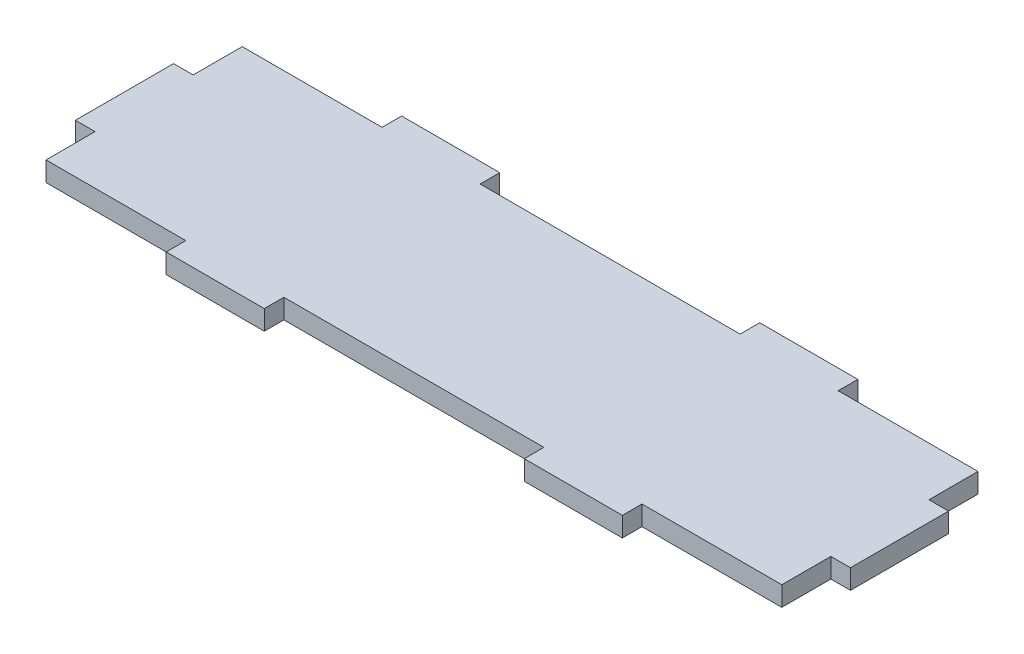
SolidWorks part; units mm, degrees
ref_plane "Alzado" through (0, 0, 0) normal (0, 0, 1) x (1, 0, 0)
ref_plane "Planta" through (0, 0, 0) normal (0, 1, 0) x (1, 0, 0)
ref_plane "Vista lateral" through (0, 0, 0) normal (1, 0, 0) x (0, 0, -1)
sketch "Croquis1" plane through (0, 0, 0) normal (0, 1, 0) x (1, 0, 0)
  line L0 (75, 0) -> (75, 40) construction
  line L1 (0, 0) -> (28.5, 0)
  line L2 (0, 0) -> (0, 10)
  line L3 (0, 40) -> (28.5, 40)
  line L4 (150, 0) -> (150, 10)
  line L6 (28.5, 40) -> (28.5, 44)
  line L7 (28.5, 44) -> (48.5, 44)
  line L8 (48.5, 40) -> (48.5, 44)
  line L10 (28.5, 0) -> (28.5, -4)
  line L11 (28.5, -4) -> (48.5, -4)
  line L12 (48.5, 0) -> (48.5, -4)
  line L13 (0, 10) -> (-4, 10)
  line L15 (0, 30) -> (-4, 30)
  line L16 (-4, 10) -> (-4, 30)
  line L17 (75, 20) -> (0, 20) construction
  line L18 (-4, 20) -> (0, 20) construction
  line L19 (37.5, 20) -> (37.5, 44) construction
  line L20 (37.5, 20) -> (37.5, -4) construction
  line L21 (121.5, 40) -> (121.5, 44)
  line L22 (101.5, 40) -> (101.5, 44)
  line L23 (121.5, 44) -> (101.5, 44)
  line L24 (101.5, 0) -> (101.5, -4)
  line L25 (121.5, -4) -> (101.5, -4)
  line L26 (121.5, 0) -> (121.5, -4)
  line L27 (150, 10) -> (154, 10)
  line L28 (154, 10) -> (154, 30)
  line L29 (150, 30) -> (154, 30)
  line L30 (0, 30) -> (0, 40)
  line L31 (48.5, 0) -> (101.5, 0)
  line L32 (48.5, 40) -> (101.5, 40)
  line L33 (0, 35) -> (75, 35) construction
  line L34 (75, 35) -> (150, 35) construction
  line L35 (121.5, 40) -> (150, 40)
  line L36 (150, 30) -> (150, 40)
  line L37 (121.5, 0) -> (150, 0)
  point P39 (37.5, 32)
  point P40 (37.5, 35)
  dimension "D1" = 150
  dimension "D2" = 40
  dimension "D3" = 4
  dimension "D4" = 20
  dimension "D5" = 26.5
extrude "Saliente-Extruir1" add sketch "Croquis1" along normal blind 4
